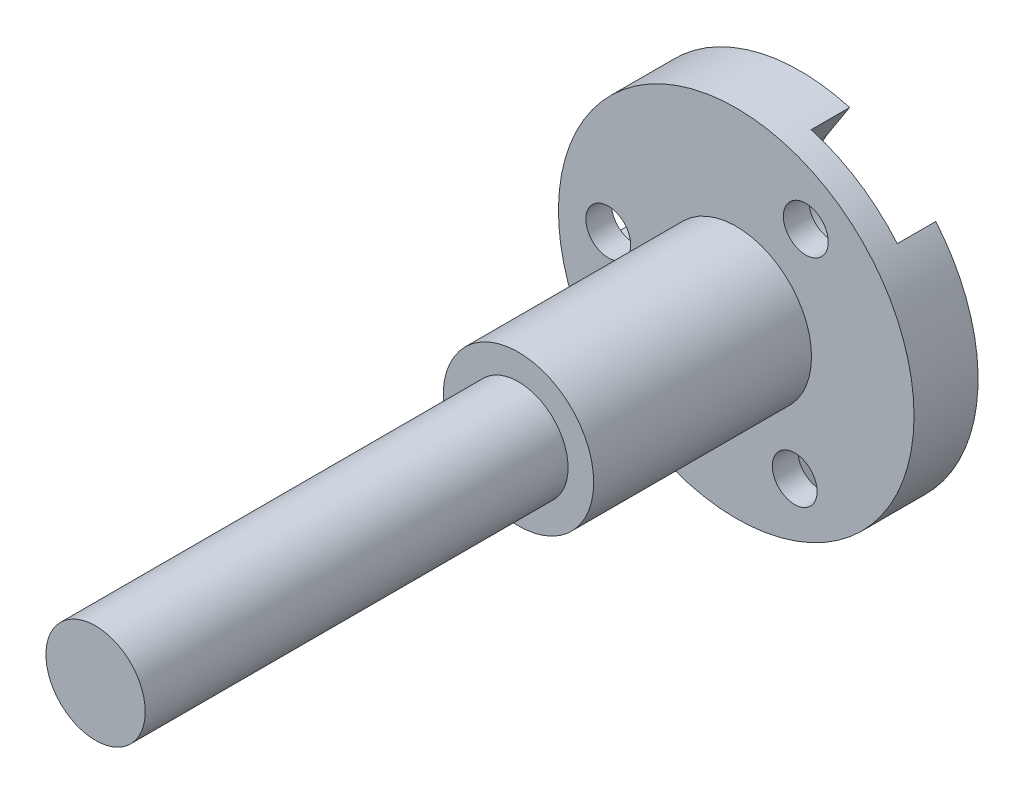
SolidWorks part; units mm, degrees
ref_plane "Plan de face" through (0, 0, 0) normal (0, 0, 1) x (1, 0, 0)
ref_plane "Plan de dessus" through (0, 0, 0) normal (0, 1, 0) x (1, 0, 0)
ref_plane "Plan de droite" through (0, 0, 0) normal (1, 0, 0) x (0, 0, -1)
sketch "Esquisse1" plane through (0, 0, 0) normal (0, 0, 1) x (1, 0, 0)
  circle A0 centre (0, 0) radius 13.875
  dimension "D1" = 27.75
extrude "Boss.-Extru.1" add sketch "Esquisse1" along normal blind 5
sketch "Esquisse2" plane through (0, 0, 0) normal (0, 0, -1) x (-1, 0, 0)
  circle A0 centre (0, 0) radius 2.625
  dimension "D1" = 5.25
extrude "Enlèv. mat.-Extru.1" cut sketch "Esquisse2" against normal blind 2
sketch "Esquisse3" plane through (0, 0, 5) normal (0, 0, 1) x (1, 0, 0)
  circle A0 centre (0, 0) radius 3.875
  dimension "D1" = 7.75
extrude "Boss.-Extru.2" add sketch "Esquisse3" along normal blind 50
sketch "Esquisse4" plane through (0, 0, 5) normal (0, 0, 1) x (1, 0, 0)
  circle A0 centre (0, 0) radius 5.875
  dimension "D1" = 11.75
extrude "Boss.-Extru.3" add sketch "Esquisse4" along normal blind 17
sketch "Esquisse5" plane through (0, 0, 0) normal (0, 0, -1) x (-1, 0, 0)
  circle A0 centre (9.9875, 0.4997) radius 1.75
  circle A1 centre (-4.561, -8.8993) radius 1.75
  circle A2 centre (-5.4265, 8.3996) radius 1.75
  dimension "D1" = 3.5
  dimension "D2" = 3.5
  dimension "D3" = 3.5
extrude "Enlèv. mat.-Extru.2" cut sketch "Esquisse5" against normal through all both and the other way through all
sketch "Esquisse6" plane through (0, 0, 0) normal (0, 0, -1) x (-1, 0, 0)
  line L0 (0, 0) -> (9.9875, 0.4997)
  line L1 (0, 0) -> (-4.561, -8.8993)
  line L2 (-5.4265, 8.3996) -> (0, 0)
  line L3 (9.9875, 0.4997) -> (15.0469, 0.7529) construction
  line L4 (9.7876, 4.4948) -> (14.847, 4.7479)
  line L5 (10.1874, -3.4953) -> (15.2468, -3.2421)
  line L6 (-4.561, -8.8993) -> (-7.8227, -15.2635) construction
  line L7 (-1.0012, -10.7237) -> (-4.2629, -17.0879)
  line L8 (-8.1207, -7.0749) -> (-11.3824, -13.4391)
  line L9 (-5.4265, 8.3996) -> (-9.8483, 15.2438) construction
  line L10 (-8.7864, 6.2289) -> (-13.2081, 13.0732)
  line L11 (-2.0667, 10.5702) -> (-6.4885, 17.4144)
  arc A3 (9.7876, 4.4948) -> (10.1874, -3.4953) centre (9.9875, 0.4997) ccw
  arc A4 (15.2468, -3.2421) -> (14.847, 4.7479) centre (15.0469, 0.7529) ccw
  arc A5 (-1.0012, -10.7237) -> (-8.1207, -7.0749) centre (-4.561, -8.8993) ccw
  arc A6 (-11.3824, -13.4391) -> (-4.2629, -17.0879) centre (-7.8227, -15.2635) ccw
  arc A7 (-8.7864, 6.2289) -> (-2.0667, 10.5702) centre (-5.4265, 8.3996) ccw
  arc A8 (-6.4885, 17.4144) -> (-13.2081, 13.0732) centre (-9.8483, 15.2438) ccw
  point P11 (-6.1918, -12.0814)
  point P17 (12.5172, 0.6263)
  point P27 (-7.6374, 11.8217)
  point P33 (0, 0)
extrude "Enlèv. mat.-Extru.3" cut sketch "Esquisse6" against normal blind 3
